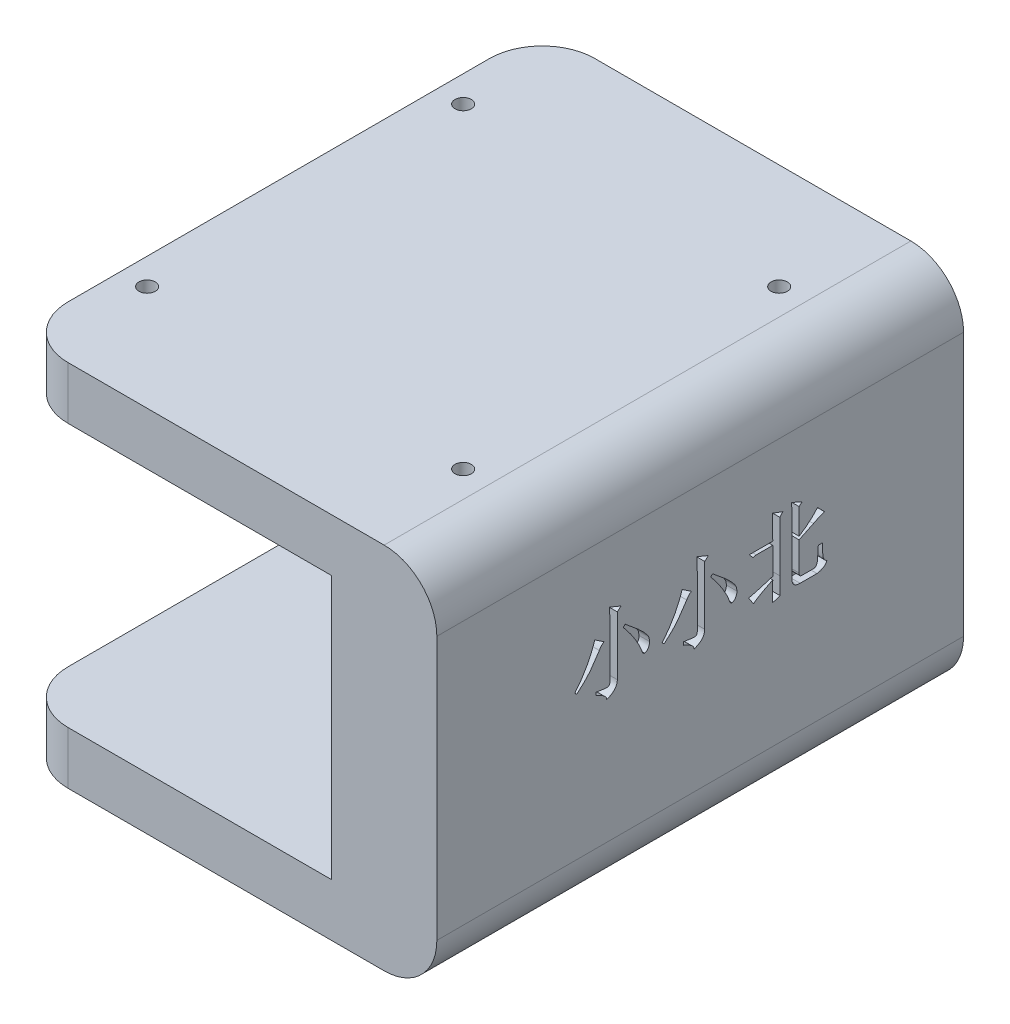
SolidWorks part; units mm, degrees
ref_plane "Front Plane" through (0, 0, 0) normal (0, 0, 1) x (1, 0, 0)
ref_plane "Top Plane" through (0, 0, 0) normal (0, 1, 0) x (1, 0, 0)
ref_plane "Right Plane" through (0, 0, 0) normal (1, 0, 0) x (0, 0, -1)
other "Configuration Table"
sketch "草图1" plane through (0, 0, 0) normal (0, 0, 1) x (1, 0, 0)
  line L0 (0, 0) -> (0, 10)
  line L1 (0, 10) -> (70, 10)
  line L2 (70, 10) -> (70, -60)
  line L3 (70, -60) -> (0, -60)
  line L4 (0, -60) -> (0, -50)
  line L5 (0, -50) -> (60, -50)
  line L6 (60, -50) -> (60, 0)
  line L7 (60, 0) -> (0, 0)
  dimension "D1" = 10
  dimension "D2" = 10
  dimension "D3" = 60
  dimension "D4" = 10
  dimension "D5" = 50
extrude "凸台-拉伸1" add sketch "草图1" along normal blind 100
sketch "草图2" plane through (0, 10, 0) normal (0, 1, 0) x (1, 0, 0)
  line L0 (0, -50) -> (70, -50) construction
  line L1 (0, -100) -> (0, 0) construction
  line L2 (70, -100) -> (70, 0) construction
  line L4 (0, -85) -> (70, -85)
  line L5 (0, -85) -> (0, -15)
  line L6 (0, -15) -> (70, -15)
  line L7 (70, -85) -> (70, -15)
  line L8 (0, -85) -> (70, -15) construction
  line L9 (0, -15) -> (70, -85) construction
  circle A0 centre (5, -20) radius 1.55
  circle A1 centre (65, -20) radius 1.55
  circle A2 centre (65, -80) radius 1.55
  circle A3 centre (5, -80) radius 1.55
  point P6 (0, -50)
  point P7 (35, -50)
  point P23 (35, -50)
  dimension "D2" = 30
  dimension "D3" = 3.1
  dimension "D1" = 70
  dimension "D4" = 4
extrude "切除-拉伸1" cut sketch "草图2" against normal up to surface (10 mm away) contours A0 | A1 | A2 | A3 up to face at (30, 0, 50)
sketch "草图3" plane through (0, -60, 0) normal (0, -1, 0) x (1, 0, 0)
  line L0 (0, 50) -> (70, 50) construction
  line L1 (0, 100) -> (0, 0) construction
  line L2 (70, 100) -> (70, 0) construction
  line L3 (35, 100) -> (35, 0) construction
  line L4 (0, 100) -> (70, 100) construction
  line L5 (0, 0) -> (70, 0) construction
  line L13 (39.3301, 52.5) -> (35, 55) construction
  line L14 (35, 55) -> (30.6699, 52.5) construction
  line L15 (30.6699, 52.5) -> (30.6699, 47.5) construction
  line L16 (30.6699, 47.5) -> (35, 45) construction
  line L17 (35, 45) -> (39.3301, 47.5) construction
  line L18 (39.3301, 47.5) -> (39.3301, 52.5) construction
  line L24 (25, 55) -> (20.6699, 52.5)
  line L25 (20.6699, 52.5) -> (20.6699, 47.5)
  line L26 (20.6699, 47.5) -> (25, 45)
  line L27 (25, 45) -> (29.3301, 47.5)
  line L28 (29.3301, 52.5) -> (25, 55)
  line L29 (29.3301, 47.5) -> (29.3301, 52.5)
  circle A0 centre (35, 50) radius 4.3301 construction
  dimension "D1" = 5
  dimension "D3" = 2
  dimension "D2" = 2
extrude "切除-拉伸2" cut sketch "草图3" against normal up to next
sketch "草图6" plane through (70, 0, 0) normal (1, 0, 0) x (0, 0, -1)
  line L4 (0, -60) -> (0, 10)
  line L5 (0, 10) -> (-100, 10)
  line L6 (-100, 10) -> (-100, -60)
  line L7 (-100, -60) -> (0, -60)
  line L8 (0, -60) -> (0, 10)
  line L9 (0, 10) -> (-100, 10)
  line L10 (-100, 10) -> (-100, -60)
  line L11 (-100, -60) -> (0, -60)
  dimension "D1" = 0
extrude "凸台-拉伸2" add sketch "草图6" along normal blind 10
fillet "圆角3" radius 10 6 edges at (0, 5, 100) (0, 5, 0) (0, -55, 100) (0, -55, 0) (80, -60, 50) (80, 10, 50)
sketch "草图7" plane through (80, 0, 0) normal (1, 0, 0) x (0, 0, -1)
  line L0 (-100, -25) -> (0, -25) construction
  line L1 (-100, 0) -> (-100, -50) construction
  line L2 (0, -50) -> (0, 0) construction
  text T0 "小小北" font "Comic Sans MS" height in points 48
extrude "切除-拉伸5" cut sketch "草图7" against normal blind 2
